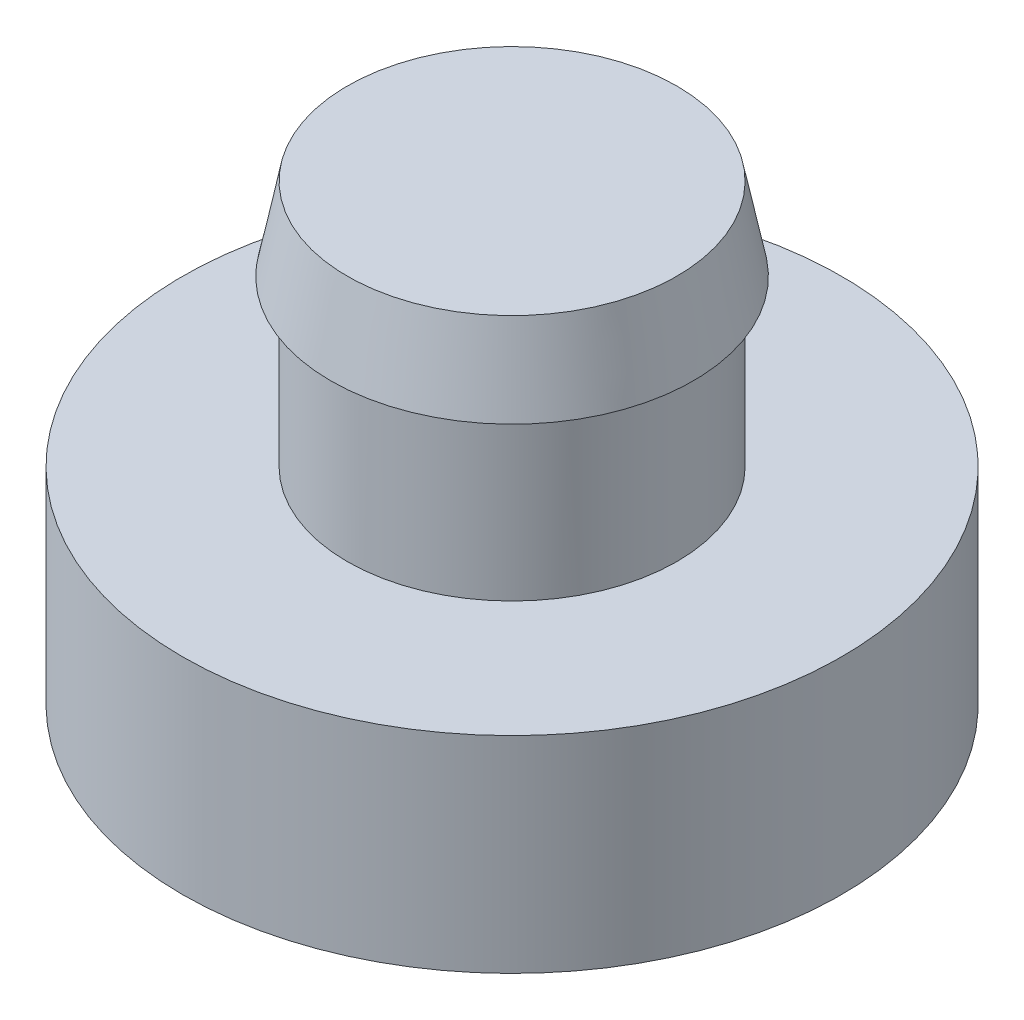
SolidWorks part; units mm, degrees
ref_plane "Front Plane" through (0, 0, 0) normal (0, 0, 1) x (1, 0, 0)
ref_plane "Top Plane" through (0, 0, 0) normal (0, 1, 0) x (1, 0, 0)
ref_plane "Right Plane" through (0, 0, 0) normal (1, 0, 0) x (0, 0, -1)
sketch "Sketch1" plane through (0, 0, 0) normal (0, 1, 0) x (1, 0, 0)
  circle A0 centre (0, 0) radius 4
  dimension "D1" = 8
extrude "Boss-Extrude1" add sketch "Sketch1" along normal blind 2.5
sketch "Sketch2" plane through (0, 2.5, 0) normal (0, 1, 0) x (1, 0, 0)
  circle A0 centre (0, 0) radius 2
  dimension "D1" = 4
extrude "Boss-Extrude2" add sketch "Sketch2" along normal blind 3
sketch "Sketch3" plane through (0, 0, 0) normal (0, 0, 1) x (1, 0, 0)
  line L0 (2, 5.5) -> (2, 4.5)
  line L1 (2, 2.5) -> (2, 5.5) construction
  line L2 (2, 4.5) -> (2.2, 4.5)
  line L3 (2.2, 4.5) -> (2, 5.5)
  line L4 (0, 0) -> (0, 5.5) construction
  line L5 (2, 5.5) -> (-2, 5.5) construction
  dimension "D1" = 0.2
  dimension "D2" = 1
revolve "Revolve1" add sketch "Sketch3" angle 360 about L4
